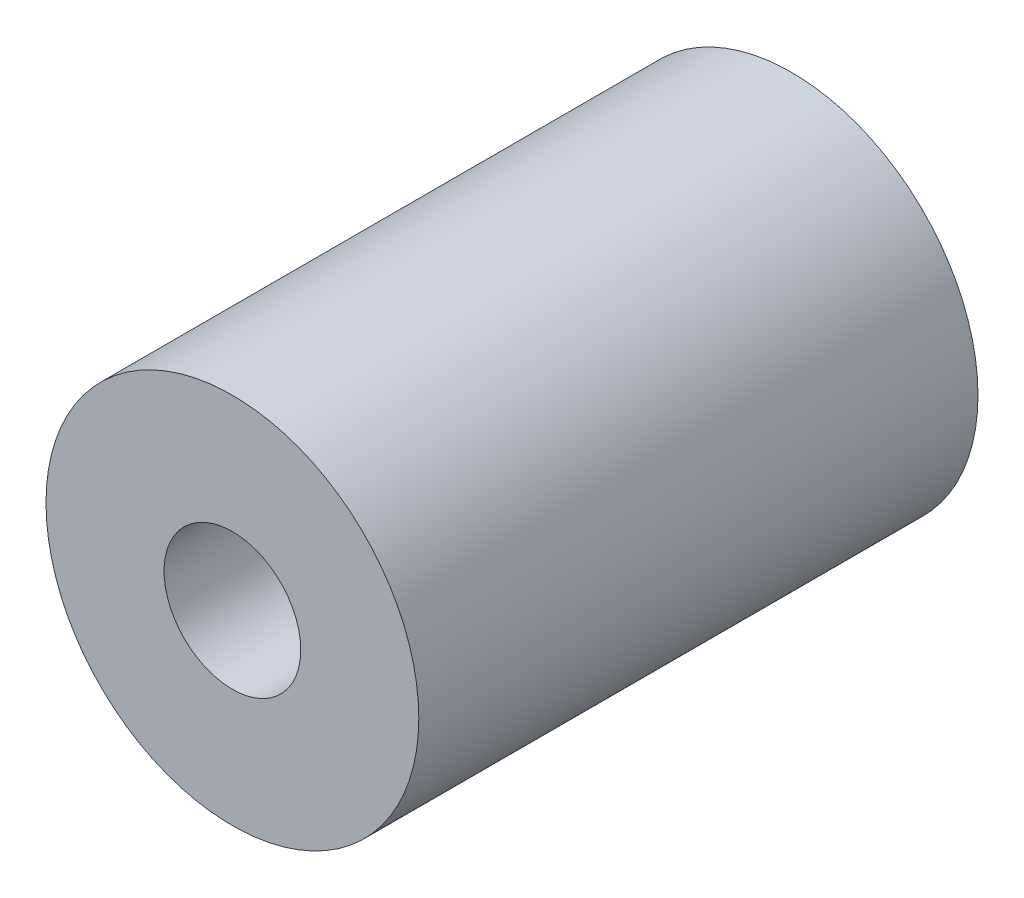
SolidWorks part; units mm, degrees
ref_plane "Front Plane" through (0, 0, 0) normal (0, 0, 1) x (1, 0, 0)
ref_plane "Top Plane" through (0, 0, 0) normal (0, 1, 0) x (1, 0, 0)
ref_plane "Right Plane" through (0, 0, 0) normal (1, 0, 0) x (0, 0, -1)
sketch "Sketch1" plane through (0, 0, 0) normal (0, 0, 1) x (1, 0, 0)
  circle A0 centre (0, 0) radius 3.81
  circle A1 centre (0, 0) radius 1.397
  dimension "D1" = 7.62
  dimension "D2" = 2.794
extrude "Boss-Extrude1" add sketch "Sketch1" along normal blind 11.43
